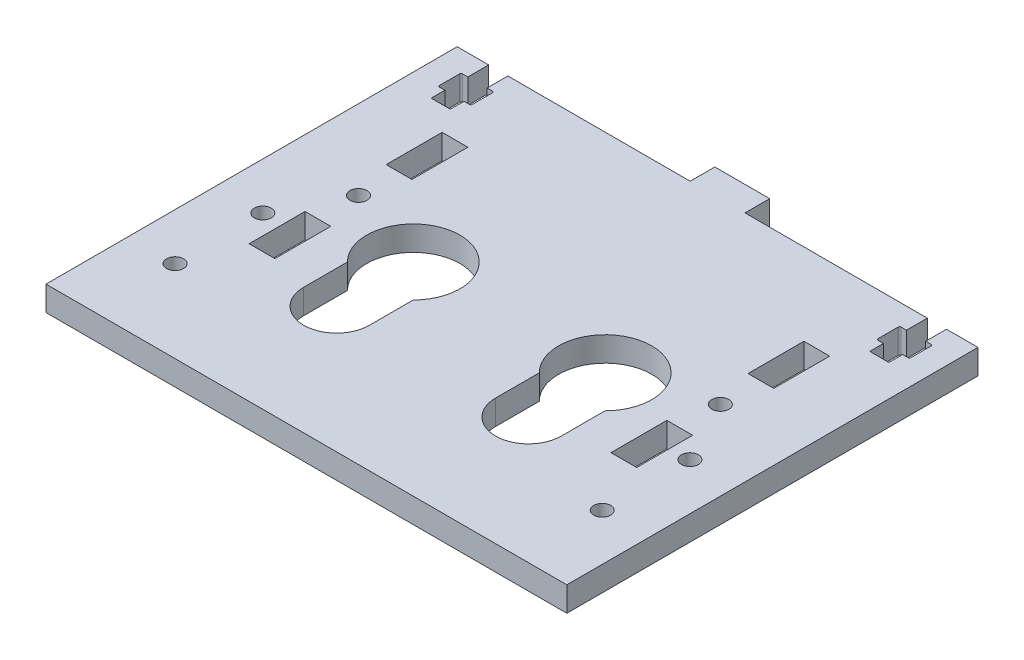
SolidWorks part; units mm, degrees
ref_plane "Front Plane" through (0, 0, 0) normal (0, 0, 1) x (1, 0, 0)
ref_plane "Top Plane" through (0, 0, 0) normal (0, 1, 0) x (1, 0, 0)
ref_plane "Right Plane" through (0, 0, 0) normal (1, 0, 0) x (0, 0, -1)
sketch "Sketch1" plane through (0, 0, 0) normal (0, 1, 0) x (1, 0, 0)
  line L1 (-47.5, 37.5) -> (47.5, 37.5)
  line L2 (-47.5, 37.5) -> (-47.5, -37.5)
  line L3 (-47.5, -37.5) -> (47.5, -37.5)
  line L4 (47.5, 37.5) -> (47.5, -37.5)
  line L5 (-47.5, 37.5) -> (47.5, -37.5) construction
  line L6 (-47.5, -37.5) -> (47.5, 37.5) construction
  point P0 (0, 0)
  dimension "D1" = 95
  dimension "D2" = 75
extrude "MainShape" add sketch "Sketch1" along normal blind 4.5
sketch "Sketch2" plane through (0, 4.5, 0) normal (0, 1, 0) x (1, 0, 0)
  line L0 (0, -37.5) -> (0, 37.5) construction
  line L1 (-47.5, -37.5) -> (47.5, -37.5) construction
  line L2 (47.5, 37.5) -> (-47.5, 37.5) construction
  line L4 (-5, 42) -> (5, 42)
  line L5 (-5, 42) -> (-5, 33)
  line L6 (-5, 33) -> (5, 33)
  line L7 (5, 42) -> (5, 33)
  line L8 (-5, 42) -> (5, 33) construction
  line L9 (-5, 33) -> (5, 42) construction
  dimension "D1" = 10
  dimension "D2" = 4.5
extrude "Tab1" add sketch "Sketch2" against normal through all
sketch "Sketch4" plane through (0, 4.5, 0) normal (0, 1, 0) x (1, 0, 0)
  line L0 (0, 42) -> (0, -37.5) construction
  line L1 (5, 42) -> (-5, 42) construction
  line L2 (-47.5, -37.5) -> (47.5, -37.5) construction
  line L3 (-40, 37.5) -> (-40, 27) construction
  line L4 (-5, 37.5) -> (-47.5, 37.5) construction
  line L5 (-38.25, 27) -> (-41.75, 27) construction
  line L6 (-41.75, 27) -> (-41.75, 37.5) construction
  line L7 (-38.25, 27) -> (-41.75, 27)
  line L8 (-41.75, 27) -> (-41.75, 29.5)
  line L9 (-41.75, 29.5) -> (-42.75, 29.5)
  line L10 (-43, 29.75) -> (-43, 33.45)
  line L11 (-42.75, 33.7) -> (-41.75, 33.7)
  line L12 (-41.75, 33.7) -> (-41.75, 37.5)
  line L13 (-41.75, 37.5) -> (-38.25, 37.5)
  line L14 (-38.25, 27) -> (-38.25, 37.5) construction
  line L15 (-38.25, 33.7) -> (-38.25, 37.5)
  line L16 (-37.25, 33.7) -> (-38.25, 33.7)
  line L17 (-37, 29.75) -> (-37, 33.45)
  line L18 (-38.25, 29.5) -> (-37.25, 29.5)
  line L19 (-38.25, 27) -> (-38.25, 29.5)
  line L20 (38.25, 27) -> (38.25, 37.5) construction
  line L21 (41.75, 27) -> (41.75, 37.5) construction
  line L22 (38.25, 27) -> (41.75, 27) construction
  line L23 (40, 37.5) -> (40, 27) construction
  line L24 (38.25, 27) -> (38.25, 29.5)
  line L25 (38.25, 29.5) -> (37.25, 29.5)
  line L26 (37, 29.75) -> (37, 33.45)
  line L27 (37.25, 33.7) -> (38.25, 33.7)
  line L28 (38.25, 33.7) -> (38.25, 37.5)
  line L29 (41.75, 37.5) -> (38.25, 37.5)
  line L30 (41.75, 33.7) -> (41.75, 37.5)
  line L31 (42.75, 33.7) -> (41.75, 33.7)
  line L32 (43, 29.75) -> (43, 33.45)
  line L33 (41.75, 29.5) -> (42.75, 29.5)
  line L34 (41.75, 27) -> (41.75, 29.5)
  line L35 (38.25, 27) -> (41.75, 27)
  arc A0 (-42.75, 29.5) -> (-43, 29.75) centre (-42.75, 29.75) cw
  arc A1 (-37, 29.75) -> (-37.25, 29.5) centre (-37.25, 29.75) cw
  arc A2 (-37.25, 33.7) -> (-37, 33.45) centre (-37.25, 33.45) cw
  arc A3 (-43, 33.45) -> (-42.75, 33.7) centre (-42.75, 33.45) cw
  arc A4 (43, 33.45) -> (42.75, 33.7) centre (42.75, 33.45) ccw
  arc A5 (37.25, 33.7) -> (37, 33.45) centre (37.25, 33.45) ccw
  arc A6 (37, 29.75) -> (37.25, 29.5) centre (37.25, 29.75) ccw
  arc A7 (42.75, 29.5) -> (43, 29.75) centre (42.75, 29.75) ccw
  point P24 (-43, 29.5)
  point P27 (-37, 29.5)
  point P30 (-37, 33.7)
  point P33 (-43, 33.7)
  point P56 (43, 33.7)
  point P57 (37, 33.7)
  point P58 (37, 29.5)
  point P59 (43, 29.5)
  dimension "D7" = 0.25
  dimension "D1" = 10.5
  dimension "D2" = 1.75
  dimension "D3" = 4.2
  dimension "D4" = 3
  dimension "D5" = 8
  dimension "D6" = 40
extrude "Cut-Extrude2" cut sketch "Sketch4" against normal through all
sketch "Sketch5" plane through (0, 4.5, 0) normal (0, 1, 0) x (1, 0, 0)
  line L0 (0, -37.5) -> (0, 42) construction
  line L1 (-47.5, -37.5) -> (47.5, -37.5) construction
  line L2 (5, 42) -> (-5, 42) construction
  line L3 (33, 37.5) -> (33, -37.5) construction
  line L4 (47.5, 37.5) -> (41.75, 37.5) construction
  line L5 (-33, 37.5) -> (-33, -37.5) construction
  line L6 (30.65, 22.6) -> (35.35, 22.6)
  line L7 (30.65, 22.6) -> (30.65, 12.4)
  line L8 (30.65, 12.4) -> (35.35, 12.4)
  line L9 (35.35, 22.6) -> (35.35, 12.4)
  line L10 (30.65, 22.6) -> (35.35, 12.4) construction
  line L11 (30.65, 12.4) -> (35.35, 22.6) construction
  line L12 (-30.65, 12.4) -> (-35.35, 22.6) construction
  line L13 (-30.65, 22.6) -> (-35.35, 12.4) construction
  line L14 (-35.35, 22.6) -> (-35.35, 12.4)
  line L15 (-30.65, 12.4) -> (-35.35, 12.4)
  line L16 (-30.65, 22.6) -> (-30.65, 12.4)
  line L17 (-30.65, 22.6) -> (-35.35, 22.6)
  line L18 (-47.5, 5) -> (47.5, 5) construction
  line L19 (-47.5, 37.5) -> (-47.5, -37.5) construction
  line L20 (47.5, -37.5) -> (47.5, 37.5) construction
  line L21 (-30.65, -12.6) -> (-35.35, -2.4) construction
  line L22 (-30.65, -2.4) -> (-35.35, -12.6) construction
  line L23 (30.65, -2.4) -> (35.35, -12.6) construction
  line L24 (30.65, -12.6) -> (35.35, -2.4) construction
  line L25 (-30.65, -12.6) -> (-35.35, -12.6)
  line L26 (-30.65, -12.6) -> (-30.65, -2.4)
  line L27 (-30.65, -2.4) -> (-35.35, -2.4)
  line L28 (-35.35, -12.6) -> (-35.35, -2.4)
  line L29 (35.35, -12.6) -> (35.35, -2.4)
  line L30 (30.65, -2.4) -> (35.35, -2.4)
  line L31 (30.65, -12.6) -> (30.65, -2.4)
  line L32 (30.65, -12.6) -> (35.35, -12.6)
  line L33 (-30.65, 22.6) -> (-35.35, 12.4) construction
  circle A0 centre (33, 5) radius 1.55
  circle A1 centre (-33, 5) radius 1.55
  point P10 (33, 17.5)
  point P21 (-33, 17.5)
  point P36 (-33, -7.5)
  point P37 (33, -7.5)
  dimension "D6" = 3.1
  dimension "D1" = 33
  dimension "D2" = 10.2
  dimension "D3" = 4.7
  dimension "D4" = 20
  dimension "D5" = 25
extrude "Cut-Extrude3" cut sketch "Sketch5" against normal through all
sketch "Sketch6" plane through (0, 4.5, 0) normal (0, 1, 0) x (1, 0, 0)
  line L0 (-17.5, -37.5) -> (-17.5, 28) construction
  line L1 (-23.5, -14.5) -> (-23.5, -6.5208)
  line L2 (5, 42) -> (-5, 42) construction
  line L3 (-47.5, -14.5) -> (47.5, -14.5) construction
  line L4 (-47.5, 37.5) -> (-47.5, -37.5) construction
  line L5 (47.5, -37.5) -> (47.5, 37.5) construction
  line L6 (47.5, 37.5) -> (41.75, 37.5) construction
  line L7 (-47.5, -37.5) -> (47.5, -37.5) construction
  line L8 (-11.5, -14.5) -> (-11.5, -6.5208)
  line L9 (-47.5, 37.5) -> (47.5, 37.5) construction
  arc A0 (-23.5, -14.5) -> (-11.5, -14.5) centre (-17.5, -14.5) ccw
  arc A2 (-11.5, -6.5208) -> (-23.5, -6.5208) centre (-17.5, -0.5) ccw
  point P4 (0, 42)
  dimension "D1" = 12
  dimension "D6" = 8.5
  dimension "D2" = 52
  dimension "D3" = 0
  dimension "D4" = 17.5
  dimension "D5" = 0
  dimension "D7" = 14
extrude "Cut-Extrude4" cut sketch "Sketch6" against normal through all
sketch "Sketch8" plane through (0, 4.5, 0) normal (0, 1, 0) x (1, 0, 0)
  line L0 (-17.5, -8.5) -> (-17.5, -20.5) construction
  line L1 (-17.5, -14.5) -> (-38.96, -14.5) construction
  line L2 (-38.96, -22.5) -> (-38.96, -6.5) construction
  line L3 (-17.5, -20.5) -> (-17.5, -8.5) construction
  circle A0 centre (-38.96, -6.5) radius 1.55
  circle A1 centre (-17.5, -14.5) radius 6 construction
  circle A2 centre (-38.96, -22.5) radius 1.55
  dimension "D3" = 3.1
  dimension "D1" = 0
  dimension "D2" = 8
  dimension "D4" = 21.46
extrude "Cut-Extrude6" cut sketch "Sketch8" against normal through all
sketch "Sketch9" plane through (0, 4.5, 0) normal (0, 1, 0) x (1, 0, 0)
  line L0 (0, -37.5) -> (0, 42) construction
  line L1 (-47.5, -37.5) -> (47.5, -37.5) construction
  line L2 (5, 42) -> (-5, 42) construction
  line L3 (20, -37.5) -> (20, -27) construction
  line L4 (18.25, -27) -> (21.75, -27) construction
  line L5 (21.75, -27) -> (21.75, -37.5) construction
  line L6 (21.75, -37.5) -> (21.75, -33.7)
  line L7 (21.75, -33.7) -> (22.75, -33.7)
  line L8 (23, -33.45) -> (23, -29.75)
  line L9 (22.75, -29.5) -> (21.75, -29.5)
  line L10 (21.75, -29.5) -> (21.75, -27)
  line L11 (21.75, -27) -> (18.25, -27)
  line L12 (21.75, -37.5) -> (18.25, -37.5)
  line L13 (18.25, -27) -> (18.25, -37.5) construction
  line L14 (18.25, -29.5) -> (18.25, -27)
  line L15 (17.25, -29.5) -> (18.25, -29.5)
  line L16 (17, -33.45) -> (17, -29.75)
  line L17 (18.25, -33.7) -> (17.25, -33.7)
  line L18 (18.25, -37.5) -> (18.25, -33.7)
  line L19 (-18.25, -27) -> (-18.25, -37.5) construction
  line L20 (-21.75, -27) -> (-21.75, -37.5) construction
  line L21 (-18.25, -27) -> (-21.75, -27) construction
  line L22 (-20, -37.5) -> (-20, -27) construction
  line L23 (-18.25, -37.5) -> (-18.25, -33.7)
  line L24 (-18.25, -33.7) -> (-17.25, -33.7)
  line L25 (-17, -33.45) -> (-17, -29.75)
  line L26 (-17.25, -29.5) -> (-18.25, -29.5)
  line L27 (-18.25, -29.5) -> (-18.25, -27)
  line L28 (-21.75, -37.5) -> (-18.25, -37.5)
  line L29 (-21.75, -27) -> (-18.25, -27)
  line L30 (-21.75, -29.5) -> (-21.75, -27)
  line L31 (-22.75, -29.5) -> (-21.75, -29.5)
  line L32 (-23, -33.45) -> (-23, -29.75)
  line L33 (-21.75, -33.7) -> (-22.75, -33.7)
  line L34 (-21.75, -37.5) -> (-21.75, -33.7)
  arc A0 (22.75, -33.7) -> (23, -33.45) centre (22.75, -33.45) ccw
  arc A1 (23, -29.75) -> (22.75, -29.5) centre (22.75, -29.75) ccw
  arc A2 (17, -29.75) -> (17.25, -29.5) centre (17.25, -29.75) cw
  arc A3 (17.25, -33.7) -> (17, -33.45) centre (17.25, -33.45) cw
  arc A4 (-17.25, -33.7) -> (-17, -33.45) centre (-17.25, -33.45) ccw
  arc A5 (-17, -29.75) -> (-17.25, -29.5) centre (-17.25, -29.75) ccw
  arc A6 (-23, -29.75) -> (-22.75, -29.5) centre (-22.75, -29.75) cw
  arc A7 (-22.75, -33.7) -> (-23, -33.45) centre (-22.75, -33.45) cw
  point P16 (23, -33.7)
  point P19 (23, -29.5)
  point P30 (17, -29.5)
  point P31 (17, -33.7)
  point P54 (-17, -33.7)
  point P55 (-17, -29.5)
  point P56 (-23, -29.5)
  point P57 (-23, -33.7)
  dimension "D7" = 0.25
  dimension "D1" = 10.5
  dimension "D2" = 1.75
  dimension "D3" = 8
  dimension "D4" = 4.2
  dimension "D5" = 3
  dimension "D6" = 20
extrude "Cut-Extrude7" [suppressed] cut sketch "Sketch9" against normal through all
sketch "Sketch10" [suppressed] plane through (0, 0, 28) normal (0, 0, 1) x (1, 0, 0)
  line L0 (-55, 2.25) -> (55, 2.25) construction
  line L1 (-55, 4.5) -> (-55, 0) construction
  line L2 (55, 4.5) -> (55, 0) construction
  line L3 (-16, 4.5) -> (-16, 0) construction
  line L4 (-14.25, 4.5) -> (-17.75, 4.5) construction
  line L5 (16, 4.5) -> (16, 0) construction
  line L6 (17.75, 4.5) -> (14.25, 4.5) construction
  line L7 (17.75, 0) -> (14.25, 0) construction
  line L8 (-14.25, 0) -> (-17.75, 0) construction
  circle A0 centre (-16, 2.25) radius 1.6
  circle A1 centre (16, 2.25) radius 1.6
  dimension "D1" = 3.2
  dimension "D2" = 3.2
mirror "Mirror1" about plane through (0, 0, 0) normal (1, 0, 0) of "Cut-Extrude6", "Cut-Extrude4"
equation "\"X-ROD-SPACING\"=45"
equation "\"Y-ROD-SPACING\"=75"
equation "\"Z-ROD-SPACING\"=17.5"
equation "\"Y-BED-OFFSET\"=2"
equation "\"Y-BED-ROD-INSET\"=3.5"
equation "\"Y-BED-SCREW-SPACING\"=209"
equation "\"Y-BED-SCREW-CUTOUT-SLOT-HEIGHT\"=2"
equation "\"T-SLOT-NUT-FILLET-RADIUS\"=0.25"
equation "\"T-SLOT-SCREW-SHAFT-RADIUS\"=1.75"
equation "\"T-SLOT-SCREW-SHAFT-CUTOUT-LENGTH\"=10.5"
equation "\"T-SLOT-NUT-DEPTH\"=4.2"
equation "\"T-SLOT-NUT-WIDTH\"=3"
equation "\"T-SLOT-NUT-END-DISTANCE\"=8"
equation "\"ACRYLIC-THICKNESS\"=10"
equation "\"ACRYLIC-THICKNESS2\"=4.5"
equation "\"ACRYLIC-TAB-CUTOUT-SIZE\"=\"ACRYLIC-THICKNESS\"+\"ACRYLIC-TAB-TOLERANCE\"*2"
equation "\"ACRYLIC-TAB-WIDTH\"=\"ACRYLIC-THICKNESS\""
equation "\"ACRYLIC-M3-HOLE\"=3.1"
equation "\"SMOOTHROD-CAP-SCREW-DISTANCE\"=20"
equation "\"FRAME-WIDTH-INNER\"=370"
equation "\"NEMA17-HOLE-SPACING\"=31"
equation "\"NEMA17-CENTRAL-CUTOUT\"=22.5"
equation "\"Z-BRACKET-REACH\"=55"
equation "\"Z-ROD-INSET\"=16"
equation "\"TOP-BRACKET-SPACING\"=40"
equation "\"SMOOTHROD-X-LENGTH\"=350"
equation "\"SMOOTHROD-Y-LENGTH\"=350"
equation "\"SMOOTHROD-Z-LENGTH\"=350"
equation "\"SMOOTHROD-TIGHTENING-HEADROOM\"=.25"
equation "\"LEADSCREW-Z-LENGTH\"=300"
equation "\"SCREW-LENGTH-FRAME\"=\"ACRYLIC-THICKNESS\" + 10"
equation "\"SCREW-LENGTH-MOTOR\"=\"ACRYLIC-THICKNESS\" + 5"
equation "\"SCREW-LENGTH-EXTRUDER\"=28"
equation "\"SCREW-HEAD-RADIUS\"=6"
equation "\"PRINTED-X-SMOOTHROD-DIAMETER\"=8.2"
equation "\"PRINTED-X-SMOOTHROD-CUTOUT\"=10"
equation "\"PRINTED-X-BASE-HEIGHT\"=10"
equation "\"PRINTED-LM8UU-CUTOUT-SIZE\"=15.25"
equation "\"PRINTED-LM8UU-CUTOUT-LENGTH\"=24.5"
equation "\"PRINTED-X-IDLER-HEIGHT\"=16"
equation "\"PSU-MOUNTING-WIDTH\"=95"
equation "\"PSU-MOUNTING-HEIGHT\"=177"
equation "\"Y-BELT-TO-ROD-DISTANCE\"=20"
equation "\"SPOOL-HOLDER-ROD-SPACING\"=150"
equation "\"ACRYLIC-X-CARRIAGE-WIDTH\"=55"
equation "\"ACRYLIC-X-CARRIAGE-HEIGHT\"=75"
equation "\"ACRYLIC-X-CARRIAGE-SCREW-SPACING-X\"=15"
equation "\"ACRYLIC-X-CARRIAGE-SCREW-SPACING-Y\"=33"
equation "\"ACRYLIC-X-CARRIAGE-CENTER-TAB-SPACING\"=14"
equation "\"D1@MainShape\" = \"ACRYLIC-THICKNESS2\""
equation "\"D1@Sketch2\"=\"ACRYLIC-TAB-WIDTH\""
equation "\"D2@Sketch2\"=\"ACRYLIC-THICKNESS2\""
equation "\"D1@Sketch4\"=\"T-SLOT-SCREW-SHAFT-CUTOUT-LENGTH\""
equation "\"D2@Sketch4\"=\"T-SLOT-SCREW-SHAFT-RADIUS\""
equation "\"D3@Sketch4\"=\"T-SLOT-NUT-DEPTH\""
equation "\"D4@Sketch4\"=\"T-SLOT-NUT-WIDTH\""
equation "\"D5@Sketch4\"=\"T-SLOT-NUT-END-DISTANCE\""
equation "\"D7@Sketch4\"=\"T-SLOT-NUT-FILLET-RADIUS\""
equation "\"ACRYLIC-X-CARRIAGE-EXTRUDER-SHELF-DEPTH\"=\"ACRYLIC-X-CARRIAGE-EXTRUDER-OFFSET\" + 28"
equation "\"ACRYLIC-X-CARRIAGE-LM8UU-CUTOUT-WIDTH\"=24.25"
equation "\"ACRYLIC-X-CARRIAGE-EXTRUDER-BRACE-SPACING\"=23"
equation "\"ACRYLIC-X-CARRIAGE-EXTRUDER-BRACE-TAB-OFFSET\"=20"
equation "\"ACRYLIC-X-CARRIAGE-EXTRUDER-BRACE-HEIGHT\"=35"
equation "\"ACRYLIC-X-CARRIAGE-EXTRUDER-BRACE-SCREW-SPACING\"=22"
equation "\"D2@Sketch5\"=\"ACRYLIC-TAB-CUTOUT-SIZE\""
equation "\"D3@Sketch5\"=\"ACRYLIC-THICKNESS2\"+\"ACRYLIC-TAB-TOLERANCE\"*2"
equation "\"D4@Sketch5\"=\"ACRYLIC-X-CARRIAGE-EXTRUDER-BRACE-TAB-OFFSET\""
equation "\"D3@Sketch8\"=\"ACRYLIC-M3-HOLE\""
equation "\"ACRYLIC-X-CARRIAGE-EXTRUDER-ANGLE\"=90"
equation "\"ACRYLIC-X-CARRIAGE-EXTRUDER-OFFSET\"=26"
equation "\"D6@Sketch5\"=\"ACRYLIC-M3-HOLE\""
equation "\"D1@Sketch9\"=\"T-SLOT-SCREW-SHAFT-CUTOUT-LENGTH\""
equation "\"D2@Sketch9\"=\"T-SLOT-SCREW-SHAFT-RADIUS\""
equation "\"D3@Sketch9\"=\"T-SLOT-NUT-END-DISTANCE\""
equation "\"D4@Sketch9\"=\"T-SLOT-NUT-DEPTH\""
equation "\"D5@Sketch9\"=\"T-SLOT-NUT-WIDTH\""
equation "\"D7@Sketch9\"=\"T-SLOT-NUT-FILLET-RADIUS\""
equation "\"ACRYLIC-TAB-TOLERANCE\"=.1"
equation "\"ACRYLIC-X-CARRIAGE-DUAL-WIDTH-MULTIPLIER\"=1.65"
equation "\"ACRYLIC-X-CARRIAGE-DUAL-HOTEND-SPACING\"=42"
equation "\"ACRYLIC-X-CARRIAGE-DUAL-WIDTH\"=95"
equation "\"ACRYLIC-X-CARRIAGE-DUAL-HOTEND-SEPARATION\"=35"
equation "\"ACRYLIC-X-CARRIAGE-DUAL-MOUNT-PLATE-DEPTH\"=75"
equation "\"ACRYLIC-X-CARRIAGE-DUAL-MOUNT-BRACE-WIDTH\"=33"
equation "\"D1@Sketch5\"=\"ACRYLIC-X-CARRIAGE-DUAL-MOUNT-BRACE-WIDTH\""
equation "\"ACRYLIC-X-CARRIAGE-DUAL-MOUNT-SCREW-WIDTH\"=40"
equation "\"D6@Sketch4\"=\"ACRYLIC-X-CARRIAGE-DUAL-MOUNT-SCREW-WIDTH\""
equation "\"D1@Sketch1\"=\"ACRYLIC-X-CARRIAGE-DUAL-WIDTH\""
equation "\"D2@Sketch1\"=\"ACRYLIC-X-CARRIAGE-DUAL-MOUNT-PLATE-DEPTH\""
equation "\"D4@Sketch6\"=\"ACRYLIC-X-CARRIAGE-DUAL-HOTEND-SEPARATION\"/2"
